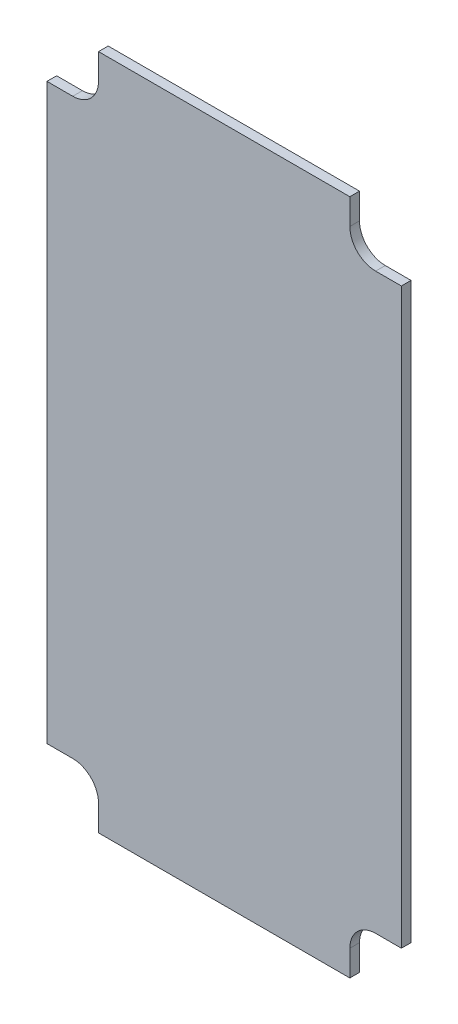
SolidWorks part; units mm, degrees
ref_plane "Alzado" through (0, 0, 0) normal (0, 0, 1) x (1, 0, 0)
ref_plane "Planta" through (0, 0, 0) normal (0, 1, 0) x (1, 0, 0)
ref_plane "Vista lateral" through (0, 0, 0) normal (1, 0, 0) x (0, 0, -1)
sketch "Croquis1" plane through (0, 0, 0) normal (0, 0, 1) x (1, 0, 0)
  line L1 (-27.5, -52.5) -> (27.5, -52.5)
  line L2 (-27.5, -52.5) -> (-27.5, 52.5)
  line L3 (-27.5, 52.5) -> (27.5, 52.5)
  line L4 (27.5, -52.5) -> (27.5, 52.5)
  line L5 (-27.5, -52.5) -> (27.5, 52.5) construction
  line L6 (-27.5, 52.5) -> (27.5, -52.5) construction
  point P0 (0, 0)
  dimension "D1" = 105
  dimension "D2" = 55
extrude "Saliente-Extruir1" add sketch "Croquis1" along normal blind 1.5
sketch "Croquis2" plane through (0, 0, 1.5) normal (0, 0, 1) x (1, 0, 0)
  line L0 (-27.5, -48.5) -> (27.5, -48.5) construction
  line L1 (-27.5, 52.5) -> (-27.5, -52.5) construction
  line L2 (27.5, -52.5) -> (27.5, 52.5) construction
  line L3 (-23.5, -52.5) -> (-23.5, 52.5) construction
  line L4 (-27.5, -52.5) -> (27.5, -52.5) construction
  line L5 (27.5, 52.5) -> (-27.5, 52.5) construction
  line L6 (23.5, -52.5) -> (23.5, 52.5) construction
  line L7 (-27.5, 48.5) -> (27.5, 48.5) construction
  line L8 (-19.5, -48.5) -> (-19.5, -52.5)
  line L9 (-23.5, -44.5) -> (-27.5, -44.5)
  line L10 (19.5, -48.5) -> (19.5, -52.5)
  line L11 (23.5, -44.5) -> (27.5, -44.5)
  line L12 (19.5, 48.5) -> (19.5, 52.5)
  line L13 (23.5, 44.5) -> (27.5, 44.5)
  line L14 (-19.5, 48.5) -> (-19.5, 52.5)
  line L15 (-23.5, 44.5) -> (-27.5, 44.5)
  line L16 (-27.5, 44.5) -> (-27.5, 52.5)
  line L17 (-27.5, 52.5) -> (-19.5, 52.5)
  line L18 (19.5, 52.5) -> (27.5, 52.5)
  line L19 (27.5, 52.5) -> (27.5, 44.5)
  line L20 (19.5, -52.5) -> (27.5, -52.5)
  line L21 (27.5, -52.5) -> (27.5, -44.5)
  line L22 (-19.5, -52.5) -> (-27.5, -52.5)
  line L23 (-27.5, -52.5) -> (-27.5, -44.5)
  arc A0 (-23.5, -44.5) -> (-19.5, -48.5) centre (-23.5, -48.5) cw
  arc A1 (23.5, -44.5) -> (19.5, -48.5) centre (23.5, -48.5) ccw
  arc A2 (23.5, 44.5) -> (19.5, 48.5) centre (23.5, 48.5) cw
  arc A3 (-23.5, 44.5) -> (-19.5, 48.5) centre (-23.5, 48.5) ccw
  dimension "D5" = 4
  dimension "D6" = 4
  dimension "D7" = 4
  dimension "D8" = 4
  dimension "D1" = 4
  dimension "D2" = 4
  dimension "D3" = 4
  dimension "D4" = 4
extrude "Cortar-Extruir1" cut sketch "Croquis2" against normal up to next
equation "\"D2@Croquis2\"=\"D1@Croquis2\""
equation "\"D3@Croquis2\"=\"D1@Croquis2\""
equation "\"D4@Croquis2\"=\"D1@Croquis2\""
